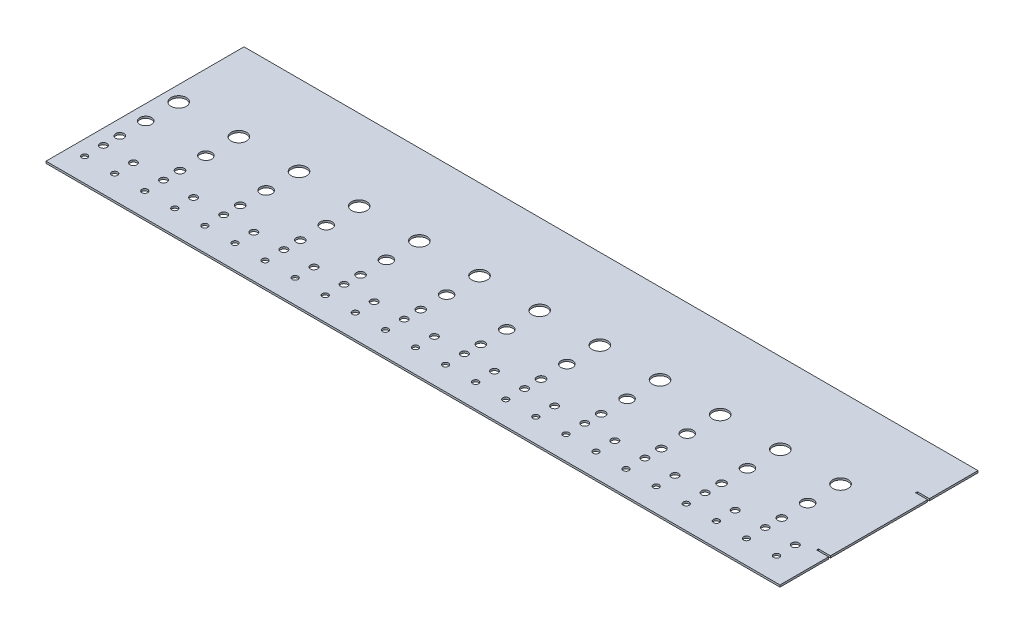
SolidWorks part; units mm, degrees
ref_plane "Front Plane" through (0, 0, 0) normal (0, 0, 1) x (1, 0, 0)
ref_plane "Top Plane" through (0, 0, 0) normal (0, 1, 0) x (1, 0, 0)
ref_plane "Right Plane" through (0, 0, 0) normal (1, 0, 0) x (0, 0, -1)
sketch "Sketch1" plane through (0, 0, 0) normal (0, 1, 0) x (1, 0, 0)
  line L1 (0, 0) -> (306.8972, 0)
  line L2 (0, 0) -> (0, 84.1681)
  line L3 (0, 84.1681) -> (306.8972, 84.1681)
  line L4 (306.8972, 0) -> (306.8972, 84.1681)
  circle A0 centre (6.3937, 10) radius 1.25
  circle A1 centre (19.1811, 10) radius 1.25
  circle A2 centre (31.9684, 10) radius 1.25
  circle A3 centre (44.7558, 10) radius 1.25
  circle A4 centre (57.5432, 10) radius 1.25
  circle A5 centre (70.3306, 10) radius 1.25
  circle A6 centre (83.1179, 10) radius 1.25
  circle A7 centre (95.9053, 10) radius 1.25
  circle A8 centre (108.6927, 10) radius 1.25
  circle A9 centre (121.4801, 10) radius 1.25
  circle A10 centre (134.2675, 10) radius 1.25
  circle A11 centre (147.0548, 10) radius 1.25
  circle A12 centre (159.8422, 10) radius 1.25
  circle A13 centre (172.6296, 10) radius 1.25
  circle A14 centre (185.417, 10) radius 1.25
  circle A15 centre (198.2043, 10) radius 1.25
  circle A16 centre (210.9917, 10) radius 1.25
  circle A17 centre (223.7791, 10) radius 1.25
  circle A18 centre (236.5665, 10) radius 1.25
  circle A19 centre (249.3538, 10) radius 1.25
  circle A20 centre (262.1412, 10) radius 1.25
  circle A21 centre (274.9286, 10) radius 1.25
  circle A22 centre (287.716, 10) radius 1.25
  circle A23 centre (300.5033, 10) radius 1.25
  circle A24 centre (6.3937, 18) radius 1.5
  circle A25 centre (19.1811, 18) radius 1.5
  circle A26 centre (31.9684, 18) radius 1.5
  circle A27 centre (44.7558, 18) radius 1.5
  circle A28 centre (57.5432, 18) radius 1.5
  circle A29 centre (70.3306, 18) radius 1.5
  circle A30 centre (83.1179, 18) radius 1.5
  circle A31 centre (95.9053, 18) radius 1.5
  circle A32 centre (108.6927, 18) radius 1.5
  circle A33 centre (121.4801, 18) radius 1.5
  circle A34 centre (134.2675, 18) radius 1.5
  circle A35 centre (147.0548, 18) radius 1.5
  circle A36 centre (159.8422, 18) radius 1.5
  circle A37 centre (172.6296, 18) radius 1.5
  circle A38 centre (185.417, 18) radius 1.5
  circle A39 centre (198.2043, 18) radius 1.5
  circle A40 centre (210.9917, 18) radius 1.5
  circle A41 centre (223.7791, 18) radius 1.5
  circle A42 centre (236.5665, 18) radius 1.5
  circle A43 centre (249.3538, 18) radius 1.5
  circle A44 centre (262.1412, 18) radius 1.5
  circle A45 centre (274.9286, 18) radius 1.5
  circle A46 centre (287.716, 18) radius 1.5
  circle A47 centre (300.5033, 18) radius 1.5
  circle A48 centre (6.3937, 25) radius 1.75
  circle A49 centre (31.9685, 25) radius 1.75
  circle A50 centre (57.5432, 25) radius 1.75
  circle A51 centre (83.118, 25) radius 1.75
  circle A52 centre (108.6927, 25) radius 1.75
  circle A53 centre (134.2675, 25) radius 1.75
  circle A54 centre (159.8423, 25) radius 1.75
  circle A55 centre (185.417, 25) radius 1.75
  circle A56 centre (210.9918, 25) radius 1.75
  circle A57 centre (236.5666, 25) radius 1.75
  circle A58 centre (262.1413, 25) radius 1.75
  circle A59 centre (287.7161, 25) radius 1.75
  circle A60 centre (6.3937, 36) radius 2.5
  circle A61 centre (31.9684, 36) radius 2.5
  circle A62 centre (57.5432, 36) radius 2.5
  circle A63 centre (83.1179, 36) radius 2.5
  circle A64 centre (108.6927, 36) radius 2.5
  circle A65 centre (134.2675, 36) radius 2.5
  circle A66 centre (159.8422, 36) radius 2.5
  circle A67 centre (185.417, 36) radius 2.5
  circle A68 centre (210.9917, 36) radius 2.5
  circle A69 centre (236.5665, 36) radius 2.5
  circle A70 centre (262.1412, 36) radius 2.5
  circle A71 centre (287.716, 36) radius 2.5
  circle A72 centre (6.3937, 50) radius 3.25
  circle A73 centre (31.9684, 50) radius 3.25
  circle A74 centre (57.5432, 50) radius 3.25
  circle A75 centre (83.1179, 50) radius 3.25
  circle A76 centre (108.6927, 50) radius 3.25
  circle A77 centre (134.2675, 50) radius 3.25
  circle A78 centre (159.8422, 50) radius 3.25
  circle A79 centre (185.417, 50) radius 3.25
  circle A80 centre (210.9917, 50) radius 3.25
  circle A81 centre (236.5665, 50) radius 3.25
  circle A82 centre (262.1412, 50) radius 3.25
  circle A83 centre (287.716, 50) radius 3.25
  dimension "D3" = 2.5
  dimension "D9" = 3
  dimension "D12" = 3.5
  dimension "D15" = 5
  dimension "D20" = 6.5
  dimension "D1" = 84.1681
  dimension "D2" = 306.8972
  dimension "D4" = 10
  dimension "D5" = 6.3937
  dimension "D7" = 18
  dimension "D8" = 0
  dimension "D11" = 25
  dimension "D14" = 36
  dimension "D16" = 25.5748
  dimension "D17" = 12.7874
  dimension "D19" = 50
  dimension "D6" = 24
  dimension "D10" = 24
  dimension "D13" = 12
  dimension "D18" = 12
  dimension "D21" = 12
extrude "Boss-Extrude1" add sketch "Sketch1" along normal blind 0.8382
sketch "Sketch2" plane through (306.8972, 0, 0) normal (1, 0, 0) x (0, 0, -1)
  line L1 (0, 0) -> (84.1681, 0)
  line L2 (0, 0) -> (0, 0.8382)
  line L3 (0, 0.8382) -> (84.1681, 0.8382)
  line L4 (84.1681, 0) -> (84.1681, 0.8382)
extrude "Boss-Extrude2" add sketch "Sketch2" along normal blind 5.08
sketch "Sketch3" plane through (0, 0.8382, 0) normal (0, 1, 0) x (1, 0, 0)
  line L0 (311.9772, 84.1681) -> (311.9772, 0) construction
  line L1 (317.0572, 20.661) -> (306.8972, 20.661)
  line L2 (317.0572, 20.661) -> (317.0572, 21.423)
  line L3 (317.0572, 21.423) -> (306.8972, 21.423)
  line L4 (306.8972, 20.661) -> (306.8972, 21.423)
  line L5 (317.0572, 20.661) -> (306.8972, 21.423) construction
  line L6 (317.0572, 21.423) -> (306.8972, 20.661) construction
  line L7 (0, 0) -> (311.9772, 0) construction
  line L8 (317.0572, 62.7451) -> (306.8972, 62.7451)
  line L9 (317.0572, 62.7451) -> (317.0572, 63.5071)
  line L10 (317.0572, 63.5071) -> (306.8972, 63.5071)
  line L11 (306.8972, 62.7451) -> (306.8972, 63.5071)
  line L12 (317.0572, 62.7451) -> (306.8972, 63.5071) construction
  line L13 (317.0572, 63.5071) -> (306.8972, 62.7451) construction
  line L14 (311.9772, 84.1681) -> (0, 84.1681) construction
  point P0 (311.9772, 21.042)
  point P7 (311.9772, 20.661)
  point P8 (0, 0)
  point P9 (0, 0)
  point P10 (311.9772, 36.7629)
  point P13 (311.9772, 63.1261)
  point P18 (311.9772, 62.7451)
  dimension "D1" = 5.08
  dimension "D2" = 0.762
  dimension "D3" = 21.042
  dimension "D4" = 5.08
  dimension "D5" = 0
  dimension "D6" = 21.042
extrude "Cut-Extrude2" cut sketch "Sketch3" against normal blind 5.08
